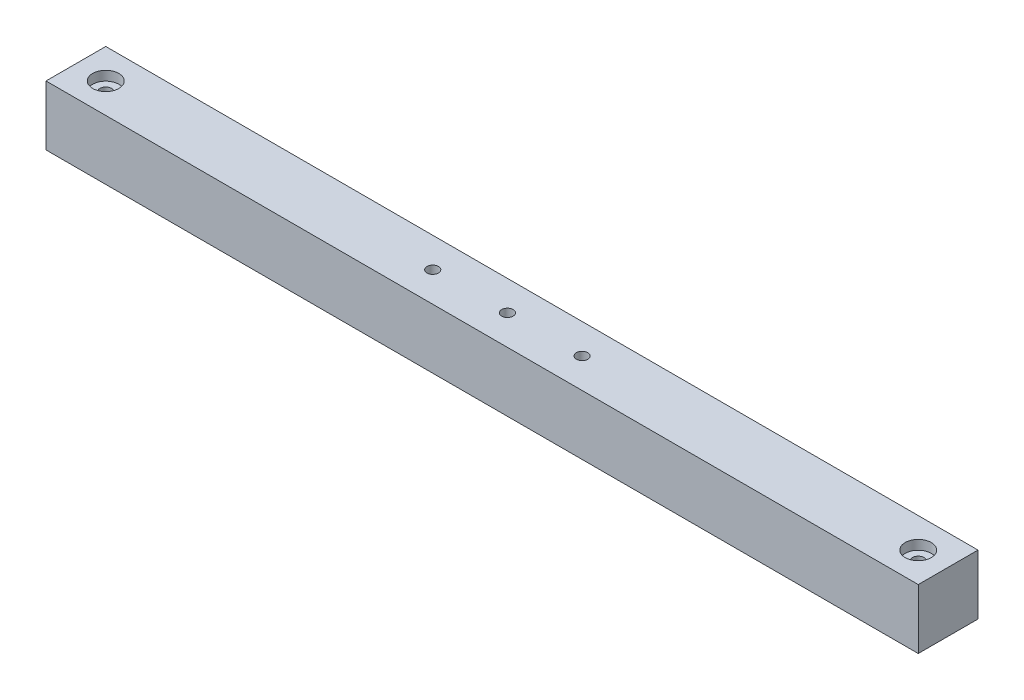
SolidWorks part; units mm, degrees
ref_plane "Front Plane" through (0, 0, 0) normal (0, 0, 1) x (1, 0, 0)
ref_plane "Top Plane" through (0, 0, 0) normal (0, 1, 0) x (1, 0, 0)
ref_plane "Right Plane" through (0, 0, 0) normal (1, 0, 0) x (0, 0, -1)
sketch "Sketch1" plane through (0, 0, 0) normal (0, 1, 0) x (1, 0, 0)
  line L1 (0, 0) -> (185.3997, 0)
  line L2 (0, 0) -> (0, 12.7)
  line L3 (0, 12.7) -> (185.3997, 12.7)
  line L4 (185.3997, 0) -> (185.3997, 12.7)
  line L5 (0, 0) -> (185.3997, 12.7) construction
  line L6 (0, 12.7) -> (185.3997, 0) construction
  point P4 (92.6998, 6.35)
  dimension "D1" = 185.3997
  dimension "D2" = 12.7
extrude "Boss-Extrude1" add sketch "Sketch1" along normal blind 12.7
sketch "Sketch4" plane through (0, 0, 0) normal (0, -1, 0) x (1, 0, 0)
  line L0 (0, 0) -> (185.3997, 0) construction
  line L1 (185.3997, -12.7) -> (172.6997, -12.7)
  line L2 (185.3997, -12.7) -> (185.3997, 0)
  line L3 (185.3997, 0) -> (172.6997, 0)
  line L4 (172.6997, -12.7) -> (172.6997, 0) construction
  line L5 (185.3997, -12.7) -> (172.6997, 0) construction
  line L6 (185.3997, 0) -> (172.6997, -12.7) construction
  line L8 (0, -12.7) -> (12.7, -12.7) construction
  line L9 (0, -12.7) -> (0, 0) construction
  line L10 (0, 0) -> (12.7, 0) construction
  line L11 (12.7, -12.7) -> (12.7, 0) construction
  line L12 (0, -12.7) -> (12.7, 0) construction
  line L13 (0, 0) -> (12.7, -12.7) construction
  circle A0 centre (179.0497, -6.35) radius 1.25
  circle A1 centre (6.35, -6.35) radius 1.25
  point P4 (179.0497, -6.35)
  point P14 (6.35, -6.35)
  dimension "D2" = 12.7
  dimension "D3" = 2.5
  dimension "D4" = 2.5
  dimension "D1" = 12.7
extrude "Cut-Extrude3" cut sketch "Sketch4" against normal through all contours A0 | A1
sketch "Sketch5" plane through (0, 12.7, 0) normal (0, -1, 0) x (1, 0, 0)
  circle A0 centre (179.0497, -6.35) radius 2.7749
  circle A1 centre (6.35, -6.35) radius 2.775
extrude "Cut-Extrude4" cut sketch "Sketch5" along normal blind 1.999
sketch "Sketch6" plane through (0, 12.7, 0) normal (0, 1, 0) x (1, 0, 0)
  line L0 (0, 6.35) -> (60.9498, 6.35) construction
  line L1 (0, 12.7) -> (0, 0) construction
  line L2 (185.3997, 6.35) -> (123.4694, 6.35) construction
  line L3 (185.3997, 0) -> (185.3997, 12.7) construction
  line L4 (185.3997, 12.7) -> (0, 12.7) construction
  line L5 (60.9498, 12.7) -> (122.489, 12.7) construction
  line L6 (60.9498, 12.7) -> (60.9498, 0) construction
  line L7 (60.9498, 0) -> (122.489, 0) construction
  line L8 (122.489, 12.7) -> (122.489, 0) construction
  line L9 (60.9498, 12.7) -> (122.489, 0) construction
  line L10 (60.9498, 0) -> (122.489, 12.7) construction
  line L11 (0, 0) -> (185.3997, 0) construction
  line L12 (91.7194, 6.35) -> (75.8444, 6.35) construction
  line L13 (107.5944, 6.35) -> (91.7194, 6.35) construction
  line L15 (123.4694, 6.35) -> (107.5944, 6.35) construction
  circle A5 centre (91.7194, 6.35) radius 1.2192
  circle A6 centre (107.5944, 6.35) radius 1.2192
  circle A7 centre (75.8444, 6.35) radius 1.2192
  point P12 (91.7194, 6.35)
  dimension "D3" = 15.875
  dimension "D4" = 2.4384
  dimension "D5" = 2.4384
  dimension "D1" = 15.875
  dimension "D2" = 61.9303
  dimension "D7" = 15.875
  dimension "D8" = 15.875
extrude "Cut-Extrude5" cut sketch "Sketch6" against normal through all
